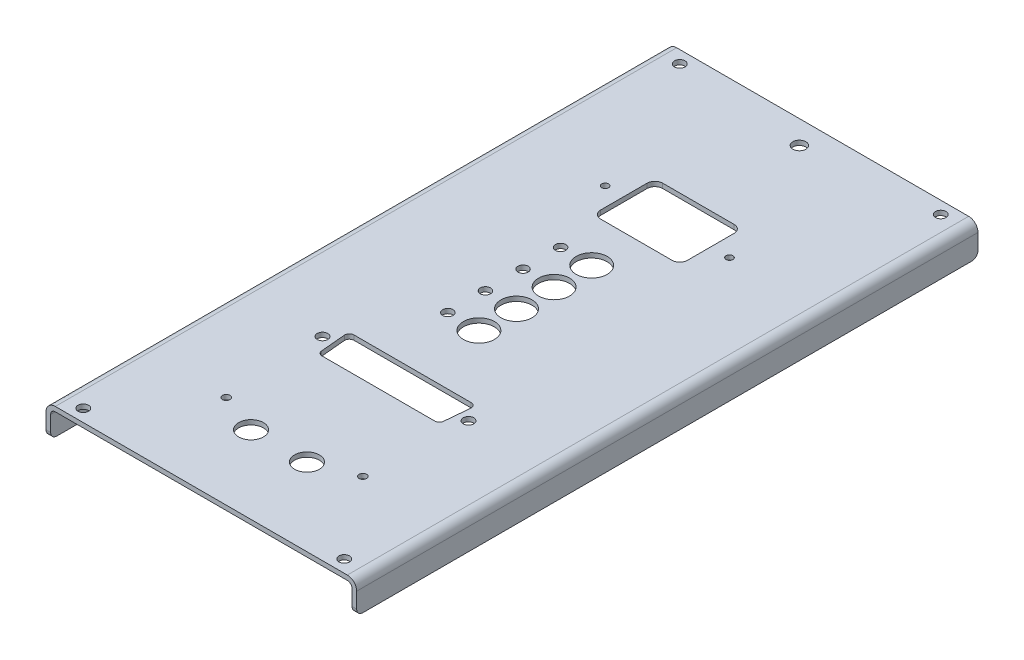
SolidWorks part; units mm, degrees
ref_plane "Спереди" through (0, 0, 0) normal (0, 0, 1) x (1, 0, 0)
ref_plane "Сверху" through (0, 0, 0) normal (0, 1, 0) x (1, 0, 0)
ref_plane "Справа" through (0, 0, 0) normal (1, 0, 0) x (0, 0, -1)
sketch "Эскиз1" plane through (0, 0, 0) normal (0, 0, 1) x (1, 0, 0)
  line L0 (0, 24.5108) -> (0, -34.3152) construction
  line L1 (-47, 0) -> (47, 0)
  line L2 (-50, -3) -> (-50, -10)
  line L3 (50, -3) -> (50, -10)
  line L4 (-48.5, -3) -> (-48.5, -10)
  line L5 (-47, -1.5) -> (47, -1.5)
  line L6 (48.5, -3) -> (48.5, -10)
  line L7 (-50, -10) -> (-48.5, -10)
  line L8 (48.5, -10) -> (50, -10)
  arc A0 (-47, 0) -> (-50, -3) centre (-47, -3) ccw
  arc A1 (47, 0) -> (50, -3) centre (47, -3) cw
  arc A2 (-47, -1.5) -> (-48.5, -3) centre (-47, -3) ccw
  arc A3 (47, -1.5) -> (48.5, -3) centre (47, -3) cw
  point P9 (-50, 0)
  point P12 (50, 0)
  dimension "D4" = 3
  dimension "D1" = 100
  dimension "D2" = 10
  dimension "D3" = 10
  dimension "D5" = 1.5
extrude "Вытянуть1" add sketch "Эскиз1" along normal blind 200
sketch "Эскиз2" plane through (0, 0, 0) normal (0, 1, 0) x (1, 0, 0)
  line L0 (-82.3612, -100) -> (100.1076, -100) construction
  line L1 (0, 35.4265) -> (0, -316.315) construction
  line L2 (47, 0) -> (-47, 0) construction
  line L3 (47, -200) -> (-47, -200) construction
  line L4 (-50, -200) -> (-50, 0) construction
  line L5 (50, -200) -> (50, 0) construction
  circle A0 centre (-42, -4) radius 1.7
  circle A1 centre (42, -4) radius 1.7
  circle A2 centre (42, -196) radius 1.7
  circle A3 centre (-42, -196) radius 1.7
  dimension "D1" = 4
  dimension "D3" = 3.4
  dimension "D2" = 8
extrude "Вырез-Вытянуть1" cut sketch "Эскиз2" against normal blind 10
fillet "Скругление1" radius 2 4 edges at (49.25, -10, 200) (49.25, -10, 0) (-49.25, -10, 0) (-49.25, -10, 200)
sketch "Эскиз5" plane through (0, 0, 0) normal (0, 1, 0) x (-1, 0, 0)
  line L0 (-76.8323, 137.5) -> (91.8485, 137.5) construction
  line L1 (-20.3513, 133.6358) -> (-19.624, 141.6358)
  line L2 (-18.8575, 132) -> (18.8575, 132)
  line L3 (-47, 200) -> (47, 200) construction
  line L4 (-18.1302, 143) -> (18.1302, 143)
  line L5 (-26.1896, 170) -> (26.0925, 170) construction
  line L6 (20.3513, 133.6358) -> (19.624, 141.6358)
  line L7 (0, 186.7676) -> (0, 13.7731) construction
  line L9 (50, 200) -> (50, 0) construction
  circle A0 centre (-23.5, 137.5) radius 1.7
  circle A1 centre (23.5, 137.5) radius 1.7
  arc A2 (-18.8575, 132) -> (-20.3513, 133.6358) centre (-18.8575, 133.5) cw
  arc A3 (-18.1302, 143) -> (-19.624, 141.6358) centre (-18.1302, 141.5) ccw
  arc A4 (19.624, 141.6358) -> (18.1302, 143) centre (18.1302, 141.5) ccw
  arc A5 (18.8575, 132) -> (20.3513, 133.6358) centre (18.8575, 133.5) ccw
  circle A6 centre (-22, 170) radius 1.2
  circle A7 centre (22, 170) radius 1.2
  circle A8 centre (-9, 175) radius 4
  circle A9 centre (9, 175) radius 4
  point P14 (-20.5, 132)
  point P17 (-19.5, 143)
  point P20 (19.5, 143)
  point P23 (20.5, 132)
  dimension "D4" = 47
  dimension "D5" = 3.4
  dimension "D6" = 1.5
  dimension "D9" = 2.4
  dimension "D11" = 18
  dimension "D12" = 8
  dimension "D13" = 44
  dimension "D14" = 30
  dimension "D1" = 39
  dimension "D2" = 41
  dimension "D3" = 11
  dimension "D7" = 50
  dimension "D8" = 62.5
  dimension "D10" = 5
extrude "Вырез-Вытянуть2" cut sketch "Эскиз5" against normal blind 10
cosmetic thread "Условное изображение резьбы1" parameters "D2"=3
cosmetic thread "Условное изображение резьбы2" parameters "D2"=3
sketch "Эскиз7" plane through (0, 0, 0) normal (0, 1, 0) x (-1, 0, 0)
  line L0 (0, 214.2678) -> (0, -38.2363) construction
  line L1 (-11.5, 40) -> (11.5, 40)
  line L2 (14, 57.5) -> (14, 42.5)
  line L3 (-11.5, 60) -> (11.5, 60)
  line L4 (-14, 57.5) -> (-14, 42.5)
  line L5 (-47, 0) -> (47, 0) construction
  line L6 (-20, 50) -> (43.022, 50) construction
  line L9 (50, 200) -> (50, 0) construction
  arc A1 (-11.5, 60) -> (-14, 57.5) centre (-11.5, 57.5) ccw
  arc A2 (14, 57.5) -> (11.5, 60) centre (11.5, 57.5) ccw
  arc A3 (-11.5, 40) -> (-14, 42.5) centre (-11.5, 42.5) cw
  arc A4 (11.5, 40) -> (14, 42.5) centre (11.5, 42.5) ccw
  circle A5 centre (20, 50) radius 1.1
  circle A6 centre (-20, 50) radius 1.1
  circle A7 centre (0, 7.5) radius 2.1
  dimension "D4" = 2.5
  dimension "D6" = 2.5
  dimension "D9" = 2.2
  dimension "D10" = 7.5
  dimension "D13" = 4.2
  dimension "D1" = 28
  dimension "D2" = 40
  dimension "D3" = 10
  dimension "D5" = 20
  dimension "D7" = 50
  dimension "D8" = 50
extrude "Вырез-Вытянуть3" cut sketch "Эскиз7" against normal blind 10
cosmetic thread "Условное изображение резьбы4" parameters "D2"=3
cosmetic thread "Условное изображение резьбы5" parameters "D2"=3
sketch "Эскиз11" plane through (0, 0, 0) normal (0, 1, 0) x (-1, 0, 0)
  line L0 (-14, 57.5) -> (-14, 42.5) construction
  line L1 (14, 42.5) -> (14, 57.5) construction
  line L2 (0, 98.55) -> (-23.4671, 98.55) construction
  line L4 (0, 86.45) -> (-23.4671, 86.45) construction
  line L5 (-65.3431, 92.5) -> (54.1145, 92.5) construction
  line L7 (0, 110.65) -> (0, 68.5021) construction
  line L9 (10, 74.35) -> (0, 74.35) construction
  line L11 (11.5, 60) -> (-11.5, 60) construction
  line L13 (0, 86.45) -> (19.6101, 86.45) construction
  line L14 (0, 110.65) -> (25.1846, 110.65) construction
  line L15 (0, 98.55) -> (21.4725, 98.55) construction
  circle A0 centre (0, 98.55) radius 5
  circle A1 centre (0, 86.45) radius 5
  circle A4 centre (0, 74.35) radius 5
  circle A6 centre (0, 110.65) radius 5
  circle A8 centre (10, 98.55) radius 1.65
  circle A9 centre (10, 74.35) radius 1.65
  circle A10 centre (10, 86.45) radius 1.65
  circle A11 centre (10, 110.65) radius 1.65
  dimension "D1" = 12.1
  dimension "D2" = 10
  dimension "D3" = 10
  dimension "D8" = 12.1
  dimension "D11" = 3.3
  dimension "D10" = 12.1
  dimension "D13" = 32.5
extrude "Вырез-Вытянуть4" cut sketch "Эскиз11" against normal blind 10
sketch "Эскиз12" plane through (-50, 0, 0) normal (-1, 0, 0) x (0, 0, 1)
  line L0 (100, 50.3797) -> (100, -45.2602) construction
  line L1 (0, -3) -> (0, -8) construction
  line L2 (200, -3) -> (200, -8) construction
  line L3 (200, 0) -> (0, 0) construction
  circle A0 centre (100, -6.5) radius 1.6
  dimension "D1" = 3.2
  dimension "D2" = 6.5
extrude "Вырез-Вытянуть5" cut sketch "Эскиз12" against normal blind 10
cosmetic thread "Условное изображение резьбы10" parameters "D2"=4
